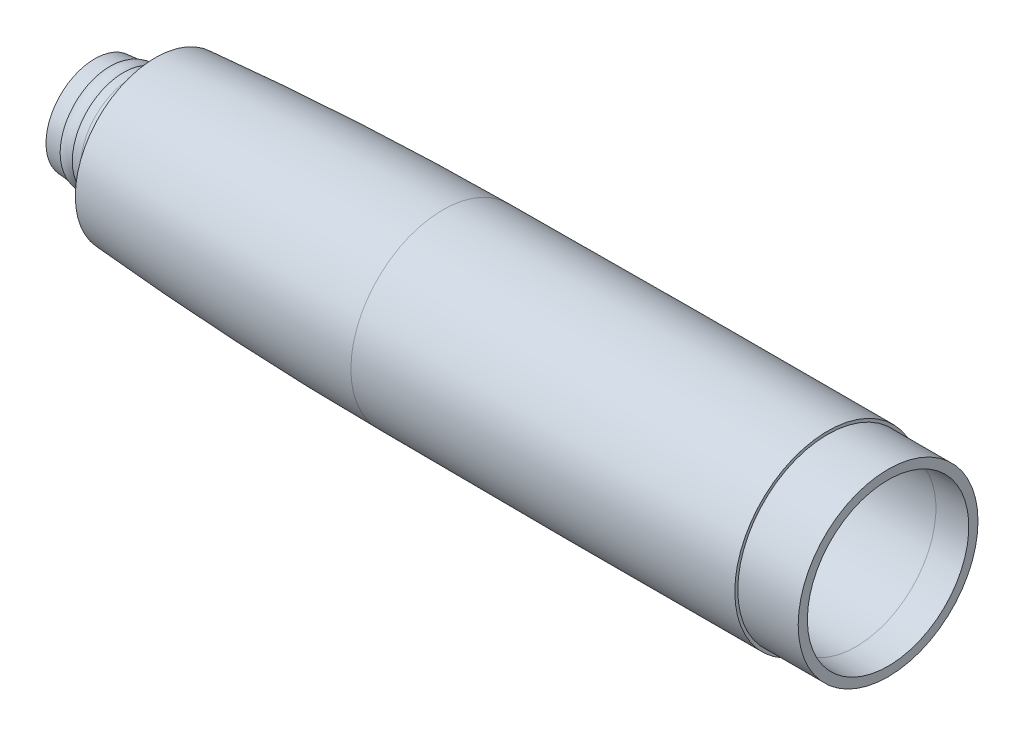
SolidWorks part; units mm, degrees
ref_plane "Plano frontal" through (0, 0, 0) normal (0, 0, 1) x (1, 0, 0)
ref_plane "Plano superior" through (0, 0, 0) normal (0, 1, 0) x (1, 0, 0)
ref_plane "Plano direito" through (0, 0, 0) normal (1, 0, 0) x (0, 0, -1)
sketch "Esboço1" plane through (0, 0, 0) normal (0, 0, 1) x (1, 0, 0)
  line L37 (9.9675, 2.815) -> (9.9675, 3.3786)
  line L38 (9.9675, 2.815) -> (11.2816, 2.815)
  line L39 (11.2816, 2.815) -> (11.2816, 3.3501)
  line L40 (11.2816, 3.3501) -> (17.8813, 3.75)
  line L41 (60.0697, 3.9776) -> (17.8813, 3.75)
  line L42 (60.0697, 3.9776) -> (60.0697, 4.9)
  line L43 (58.9869, 4.9) -> (60.0697, 4.9)
  line L44 (58.9344, 5.0958) -> (58.9869, 4.9)
  line L45 (58.8378, 5.17) -> (58.386, 5.17)
  line L46 (58.2894, 5.0958) -> (58.2369, 4.9)
  line L47 (57.4869, 4.9) -> (58.2369, 4.9)
  line L48 (57.4344, 5.0958) -> (57.4869, 4.9)
  line L49 (57.3378, 5.17) -> (56.886, 5.17)
  line L50 (56.7894, 5.0958) -> (56.7369, 4.9)
  line L51 (55.9869, 4.9) -> (56.7369, 4.9)
  line L52 (55.9344, 5.0958) -> (55.9869, 4.9)
  line L53 (55.8378, 5.17) -> (55.386, 5.17)
  line L54 (55.2894, 5.0958) -> (55.2369, 4.9)
  line L55 (54.4869, 4.9) -> (55.2369, 4.9)
  line L56 (54.4344, 5.0958) -> (54.4869, 4.9)
  line L57 (54.3378, 5.17) -> (53.886, 5.17)
  line L58 (53.7894, 5.0958) -> (53.7369, 4.9)
  line L59 (52.9869, 4.9) -> (53.7369, 4.9)
  line L60 (52.9344, 5.0958) -> (52.9869, 4.9)
  line L61 (52.8378, 5.17) -> (52.386, 5.17)
  line L62 (52.2894, 5.0958) -> (52.2369, 4.9)
  line L63 (52.2369, 4.9) -> (52.1661, 4.9)
  line L64 (52.1661, 4.9) -> (52.1661, 5.265)
  line L65 (51.1661, 5.265) -> (52.1661, 5.265)
  line L66 (49.9573, 5.5968) -> (51.1661, 5.5968)
  line L67 (49.9573, 5.5968) -> (49.2481, 5.4067)
  line L68 (49.2481, 5.4067) -> (25.8471, 5.3565)
  line L69 (20.3965, 5.2426) -> (19.6477, 5.0234)
  line L70 (19.6477, 5.0234) -> (19.0818, 5.0234)
  line L71 (18.814, 5.221) -> (19.0818, 5.0234)
  line L72 (18.4544, 5.221) -> (18.814, 5.221)
  line L73 (18.4544, 5.221) -> (17.8639, 4.9137)
  line L81 (51.1661, 5.95) -> (50.4504, 5.95)
  line L82 (51.1661, 5.5968) -> (51.1661, 6.5721)
  line L83 (50.4504, 6.3117) -> (50.4504, 5.6668)
  line L84 (50.4504, 6.3117) -> (46.2086, 6.3117)
  line L85 (46.2086, 6.5184) -> (46.2086, 6.3117)
  line L86 (46.2086, 6.5117) -> (46.4525, 6.7868)
  line L87 (50.8926, 6.7868) -> (51.1661, 6.5721)
  line L94 (48.1888, 5.6186) -> (50.4504, 5.6668)
  line L95 (26.3894, 5.6186) -> (48.1888, 5.6186)
  line L96 (26.3894, 5.6186) -> (20.1668, 5.3857)
  line L97 (0, 4.6028) -> (0, 3.1801)
  line L98 (0, 3.1801) -> (0.5992, 3.1801)
  line L99 (0.5992, 2.8945) -> (0.5992, 3.1801)
  line L102 (0, 0) -> (62.5288, 0) construction
  line L111 (-0.9896, 3.6544) -> (-0.9896, 5.6165)
  line L113 (-2.5896, 3.6544) -> (-0.9896, 3.6544)
  line L114 (-3.2216, 3.5991) -> (-2.5896, 3.6544)
  line L116 (-5.2426, 3.4223) -> (-4.1568, 3.5161)
  line L117 (-5.2426, 2.5544) -> (-5.2426, 3.4223)
  line L118 (-1.0035, 2.5544) -> (-5.2426, 2.5544)
  line L119 (0, 2.5544) -> (-5.0287, 2.5544)
  line L120 (0, 2.5544) -> (0, 0)
  line L122 (0, 0) -> (0.5992, 0)
  line L123 (51.1661, 5.5968) -> (51.1661, 5.265)
  line L124 (0.5992, 0) -> (1.3992, 0)
  line L126 (1.3992, 0) -> (1.3992, 2.3043)
  line L127 (1.3992, 2.3043) -> (6.6564, 2.3502)
  line L128 (7.6794, 2.7655) -> (9.0269, 2.7773)
  line L134 (9.6644, 2.9552) -> (9.6644, 3.2501)
  line L135 (7.5427, 3.2316) -> (9.6644, 3.2501)
  line L136 (7.2638, 2.9527) -> (7.5427, 3.2316)
  line L137 (0.5992, 2.8945) -> (7.2638, 2.9527)
  arc A13 (58.9344, 5.0958) -> (58.8378, 5.17) centre (58.8378, 5.07) ccw
  arc A14 (58.386, 5.17) -> (58.2894, 5.0958) centre (58.386, 5.07) ccw
  arc A15 (57.4344, 5.0958) -> (57.3378, 5.17) centre (57.3378, 5.07) ccw
  arc A16 (56.886, 5.17) -> (56.7894, 5.0958) centre (56.886, 5.07) ccw
  arc A17 (55.9344, 5.0958) -> (55.8378, 5.17) centre (55.8378, 5.07) ccw
  arc A18 (55.386, 5.17) -> (55.2894, 5.0958) centre (55.386, 5.07) ccw
  arc A19 (54.4344, 5.0958) -> (54.3378, 5.17) centre (54.3378, 5.07) ccw
  arc A20 (53.886, 5.17) -> (53.7894, 5.0958) centre (53.886, 5.07) ccw
  arc A21 (52.9344, 5.0958) -> (52.8378, 5.17) centre (52.8378, 5.07) ccw
  arc A22 (52.386, 5.17) -> (52.2894, 5.0958) centre (52.386, 5.07) ccw
  arc A23 (25.8471, 5.3565) -> (20.3965, 5.2426) centre (26.1589, -139.9763) ccw
  arc A24 (17.8639, 4.9137) -> (10.6506, 3.8378) centre (41.7703, -180.084) ccw
  arc A25 (10.6506, 3.8378) -> (9.9675, 3.3786) centre (10.8175, 2.8518) ccw
  arc A27 (50.8926, 6.7868) -> (46.4525, 6.7868) centre (48.6725, -15.0644) ccw
  arc A30 (18.6676, 5.2774) -> (20.1668, 5.3857) centre (19.3236, 6.6263) ccw
  arc A31 (18.6676, 5.2774) -> (0, 4.6028) centre (20.126, -293.7045) ccw
  arc A35 (46.2086, 6.5184) -> (19.2003, 6.4619) centre (39.7594, -3363.8441) ccw
  arc A36 (19.2003, 6.4619) -> (-0.9896, 5.6165) centre (20.9247, -276.2262) ccw
  arc A37 (-3.2216, 3.5991) -> (-4.1568, 3.5161) centre (-3.6111, 2.6781) ccw
  arc A38 (6.6564, 2.3502) -> (7.6794, 2.7655) centre (6.6433, 3.8501) ccw
  arc A40 (9.0269, 2.7773) -> (9.6644, 2.9552) centre (9.2449, 3.2273) ccw
sketch "Esboço2" plane through (0, 0, 0) normal (0, 0, 1) x (1, 0, 0)
  line L0 (7.6794, 2.7655) -> (9.0269, 2.7773) construction
  line L1 (9.6644, 2.9552) -> (9.6644, 3.2501) construction
  line L2 (7.5427, 3.2316) -> (9.6644, 3.2501) construction
  line L3 (7.2638, 2.9527) -> (7.5427, 3.2316) construction
  line L4 (0.5992, 2.8945) -> (7.2638, 2.9527) construction
  line L5 (1.3992, 2.3043) -> (6.6564, 2.3502) construction
  line L6 (1.3992, 0) -> (1.3992, 2.3043) construction
  line L7 (0.5992, 0) -> (1.3992, 0) construction
  line L8 (0, 2.5544) -> (0, 0) construction
  line L9 (0, 2.5544) -> (-5.0287, 2.5544) construction
  line L10 (-5.2426, 2.5544) -> (-5.2426, 3.4223) construction
  line L11 (-5.2426, 3.4223) -> (-4.1568, 3.5161) construction
  line L12 (-3.2216, 3.5991) -> (-2.5896, 3.6544) construction
  line L13 (-2.5896, 3.6544) -> (-0.9896, 3.6544) construction
  line L14 (-0.9896, 3.6544) -> (-0.9896, 5.6165) construction
  line L15 (46.2086, 6.5184) -> (46.2086, 6.3117) construction
  line L16 (50.4504, 6.3117) -> (46.2086, 6.3117) construction
  line L17 (50.4504, 6.3117) -> (50.4504, 5.6668) construction
  line L18 (48.1888, 5.6186) -> (50.4504, 5.6668) construction
  line L19 (26.3894, 5.6186) -> (48.1888, 5.6186) construction
  line L20 (26.3894, 5.6186) -> (20.1668, 5.3857) construction
  line L21 (0, 4.6028) -> (0, 3.1801) construction
  line L22 (0, 3.1801) -> (0.5992, 3.1801) construction
  line L23 (0.5992, 2.8945) -> (0.5992, 3.1801) construction
  line L24 (7.6794, 2.7655) -> (9.0269, 2.7773) construction
  line L25 (9.6644, 2.9552) -> (9.6644, 3.2501) construction
  line L26 (7.5427, 3.2316) -> (9.6644, 3.2501) construction
  line L27 (7.2638, 2.9527) -> (7.5427, 3.2316) construction
  line L28 (0.5992, 2.8945) -> (7.2638, 2.9527) construction
  line L29 (1.3992, 2.3043) -> (6.6564, 2.3502) construction
  line L30 (1.3992, 0) -> (1.3992, 2.3043)
  line L31 (0, 0) -> (1.3992, 0)
  line L32 (0, 2.5544) -> (0, 0)
  line L33 (0, 2.5544) -> (-5.2426, 2.5544)
  line L34 (-5.2426, 2.5544) -> (-5.2426, 3.4223)
  line L35 (-5.2426, 3.4223) -> (-4.1568, 3.5161)
  line L36 (-3.2216, 3.5991) -> (-2.5896, 3.6544)
  line L37 (-2.5896, 3.6544) -> (-0.9896, 3.6544)
  line L38 (-0.9896, 3.6544) -> (-0.9896, 5.6165)
  line L39 (46.2086, 6.5184) -> (46.2086, 6.3117)
  line L40 (50.4504, 6.3117) -> (46.2086, 6.3117)
  line L41 (50.4504, 6.3117) -> (50.4504, 5.6668)
  line L42 (48.1888, 5.6186) -> (50.4504, 5.6668)
  line L43 (26.3894, 5.6186) -> (48.1888, 5.6186)
  line L44 (26.3894, 5.6186) -> (20.1668, 5.3857)
  line L45 (0, 4.6028) -> (0, 3.1801)
  line L46 (0, 3.1801) -> (0.5992, 3.1801)
  line L47 (0.5992, 2.8945) -> (0.5992, 3.1801)
  line L48 (0, 0) -> (62.5288, 0) construction
  line L49 (1.3992, 2.3043) -> (1.3992, 2.9015)
  line L50 (0.5992, 2.8945) -> (1.3992, 2.9015)
  arc A0 (9.0269, 2.7773) -> (9.6644, 2.9552) centre (9.2449, 3.2273) ccw construction
  arc A1 (6.6564, 2.3502) -> (7.6794, 2.7655) centre (6.6433, 3.8501) ccw construction
  arc A2 (-3.2216, 3.5991) -> (-4.1568, 3.5161) centre (-3.6111, 2.6781) ccw construction
  arc A3 (19.2003, 6.4619) -> (-0.9896, 5.6165) centre (20.9247, -276.2262) ccw construction
  arc A4 (46.2086, 6.5184) -> (19.2003, 6.4619) centre (39.7594, -3363.8441) ccw construction
  arc A5 (18.6676, 5.2774) -> (20.1668, 5.3857) centre (19.3236, 6.6263) ccw construction
  arc A6 (18.6676, 5.2774) -> (0, 4.6028) centre (20.126, -293.7045) ccw construction
  arc A7 (9.0269, 2.7773) -> (9.6644, 2.9552) centre (9.2449, 3.2273) ccw construction
  arc A8 (6.6564, 2.3502) -> (7.6794, 2.7655) centre (6.6433, 3.8501) ccw construction
  arc A9 (-3.2216, 3.5991) -> (-4.1568, 3.5161) centre (-3.6111, 2.6781) ccw
  arc A10 (19.2003, 6.4619) -> (-0.9896, 5.6165) centre (20.9247, -276.2262) ccw
  arc A11 (46.2086, 6.5184) -> (19.2003, 6.4619) centre (39.7594, -3363.8441) ccw
  arc A12 (18.6676, 5.2774) -> (20.1668, 5.3857) centre (19.3236, 6.6263) ccw
  arc A13 (18.6676, 5.2774) -> (0, 4.6028) centre (20.126, -293.7045) ccw
revolve "Revolução1" add sketch "Esboço2" angle 360 about L48
sketch "Esboço3" plane through (0, 0, 0) normal (0, 0, 1) x (1, 0, 0)
  line L0 (11.2816, 3.3501) -> (17.8813, 3.75) construction
  line L1 (60.0697, 3.9776) -> (17.8813, 3.75) construction
  line L2 (60.0697, 3.9776) -> (60.0697, 4.9) construction
  line L3 (58.9869, 4.9) -> (60.0697, 4.9) construction
  line L4 (11.2816, 2.815) -> (11.2816, 3.3501) construction
  line L5 (9.9675, 2.815) -> (11.2816, 2.815) construction
  line L6 (9.9675, 2.815) -> (9.9675, 3.3786) construction
  line L7 (18.4544, 5.221) -> (17.8639, 4.9137) construction
  line L8 (18.4544, 5.221) -> (18.814, 5.221) construction
  line L9 (18.814, 5.221) -> (19.0818, 5.0234) construction
  line L10 (19.6477, 5.0234) -> (19.0818, 5.0234) construction
  line L11 (20.3965, 5.2426) -> (19.6477, 5.0234) construction
  line L12 (49.2481, 5.4067) -> (25.8471, 5.3565) construction
  line L13 (49.9573, 5.5968) -> (49.2481, 5.4067) construction
  line L14 (49.9573, 5.5968) -> (51.1661, 5.5968) construction
  line L15 (51.1661, 5.5968) -> (51.1661, 5.265) construction
  line L16 (51.1661, 5.265) -> (52.1661, 5.265) construction
  line L17 (52.1661, 4.9) -> (52.1661, 5.265) construction
  line L19 (11.2816, 3.3501) -> (17.8813, 3.75)
  line L20 (60.0697, 3.9776) -> (17.8813, 3.75)
  line L21 (60.0697, 3.9776) -> (60.0697, 4.9)
  line L22 (52.1661, 4.9) -> (60.0697, 4.9)
  line L23 (11.2816, 2.815) -> (11.2816, 3.3501)
  line L24 (9.9675, 2.815) -> (11.2816, 2.815)
  line L25 (9.9675, 2.815) -> (9.9675, 3.3786)
  line L26 (18.4544, 5.221) -> (17.8639, 4.9137)
  line L27 (18.4544, 5.221) -> (18.814, 5.221)
  line L28 (18.814, 5.221) -> (19.0818, 5.0234)
  line L29 (19.6477, 5.0234) -> (19.0818, 5.0234)
  line L30 (20.3965, 5.2426) -> (19.6477, 5.0234)
  line L31 (49.2481, 5.4067) -> (25.8471, 5.3565)
  line L32 (49.9573, 5.5968) -> (49.2481, 5.4067)
  line L33 (49.9573, 5.5968) -> (51.1661, 5.5968)
  line L34 (51.1661, 5.5968) -> (51.1661, 5.265)
  line L35 (51.1661, 5.265) -> (52.1661, 5.265)
  line L36 (52.1661, 4.9) -> (52.1661, 5.265)
  line L37 (58.9344, 5.0958) -> (58.9869, 4.9) construction
  line L38 (58.8378, 5.17) -> (58.386, 5.17) construction
  line L39 (58.2894, 5.0958) -> (58.2369, 4.9) construction
  line L40 (58.9344, 5.0958) -> (58.9869, 4.9)
  line L41 (58.8378, 5.17) -> (58.386, 5.17)
  line L42 (58.2894, 5.0958) -> (58.2369, 4.9)
  arc A0 (10.6506, 3.8378) -> (9.9675, 3.3786) centre (10.8175, 2.8518) ccw construction
  arc A1 (17.8639, 4.9137) -> (10.6506, 3.8378) centre (41.7703, -180.084) ccw construction
  arc A2 (25.8471, 5.3565) -> (20.3965, 5.2426) centre (26.1589, -139.9763) ccw construction
  arc A3 (10.6506, 3.8378) -> (9.9675, 3.3786) centre (10.8175, 2.8518) ccw
  arc A4 (17.8639, 4.9137) -> (10.6506, 3.8378) centre (41.7703, -180.084) ccw
  arc A5 (25.8471, 5.3565) -> (20.3965, 5.2426) centre (26.1589, -139.9763) ccw
  arc A6 (58.9344, 5.0958) -> (58.8378, 5.17) centre (58.8378, 5.07) ccw construction
  arc A7 (58.386, 5.17) -> (58.2894, 5.0958) centre (58.386, 5.07) ccw construction
  arc A8 (58.9344, 5.0958) -> (58.8378, 5.17) centre (58.8378, 5.07) ccw
  arc A9 (58.386, 5.17) -> (58.2894, 5.0958) centre (58.386, 5.07) ccw
sketch "Esboço4" plane through (0, 0, 0) normal (0, 0, 1) x (1, 0, 0)
  line L1 (-0.0285, 4.6009) -> (-0.0285, 3.1745)
  line L2 (-0.0285, 3.1745) -> (0.5853, 3.1745)
  line L3 (0.5853, 3.1745) -> (0.5853, 2.8831)
  line L4 (0.5853, 2.8831) -> (1.3992, 2.8831)
  line L5 (1.3992, 2.8831) -> (5.7275, 3.2177)
  line L6 (6.2239, 3.3955) -> (8.6, 5.0587)
  line L8 (1.3992, 2.3043) -> (1.3992, 2.9015) construction
  arc A0 (18.6676, 5.2774) -> (0, 4.6028) centre (20.126, -293.7045) ccw construction
  arc A1 (18.6676, 5.2774) -> (-0.0285, 4.6009) centre (20.126, -293.7045) ccw
  arc A2 (6.2239, 3.3955) -> (5.7275, 3.2177) centre (5.6504, 4.2147) cw
  point P3 (8.6, 5.0587)
  point P9 (6, 3.2387)
  point P19 (6, 3.2387)
  dimension "D1" = 1
extrude "Ressalto-extrusão2" add sketch "Esboço4" along normal mid plane 1 contours L6 A1 L1 L2 L3 L4 L5
pattern_circular "PadrãoCircular2" count 4 over 360 about axis through (0, 0, 0) along (1, 0, 0) of "Ressalto-extrusão2"
